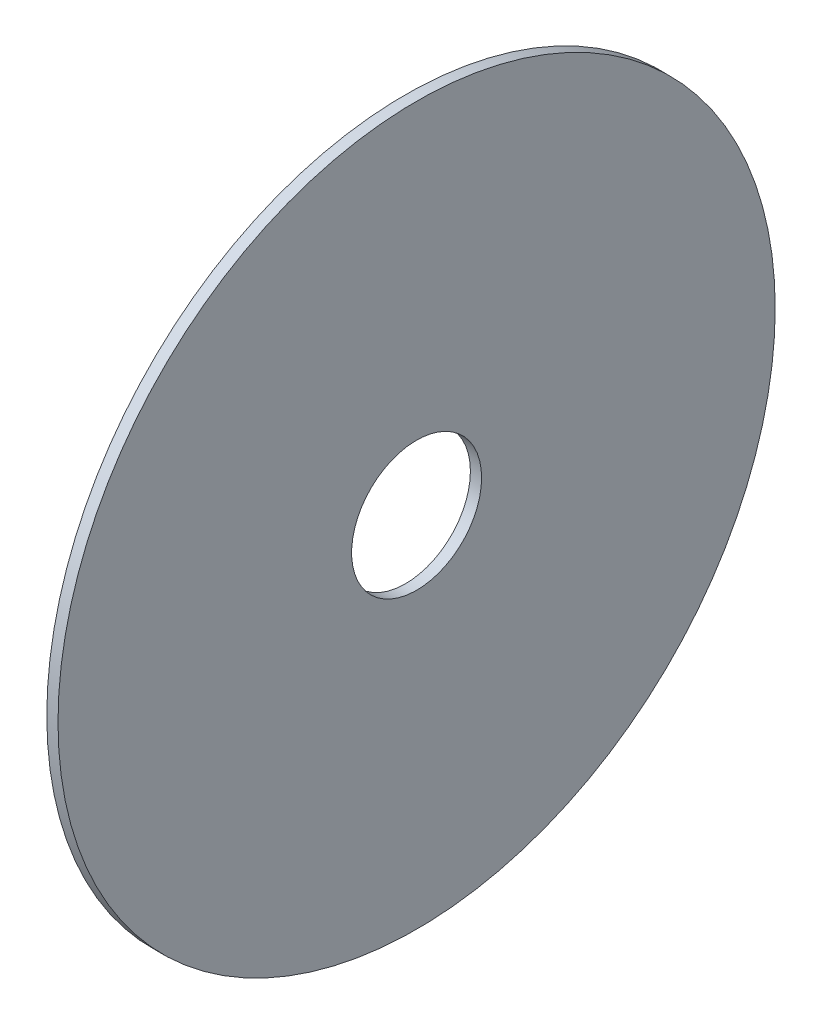
SolidWorks part; units mm, degrees
material "Plain Carbon Steel"
ref_plane "Front Plane" through (0, 0, 0) normal (0, 0, 1) x (1, 0, 0)
ref_plane "Top Plane" through (0, 0, 0) normal (0, 1, 0) x (1, 0, 0)
ref_plane "Right Plane" through (0, 0, 0) normal (1, 0, 0) x (0, 0, -1)
sketch "Sketch1" plane through (0, 0, 0) normal (1, 0, 0) x (0, 0, -1)
  circle A0 centre (0, 0) radius 50.8
  circle A1 centre (0, 0) radius 9.2075
  dimension "D1" = 18.415
  dimension "D2" = 101.6
extrude "Boss-Extrude1" add sketch "Sketch1" along normal mid plane 1.5875
